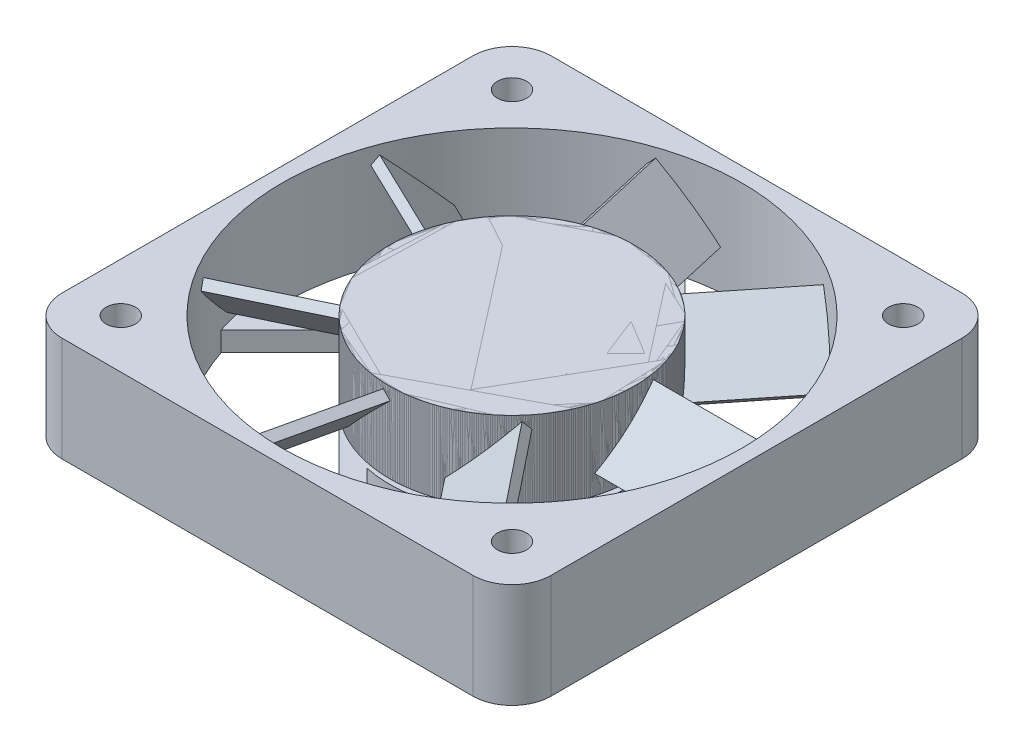
SolidWorks part; units mm, degrees
ref_plane "Front Plane" through (0, 0, 0) normal (0, 0, 1) x (1, 0, 0)
ref_plane "Top Plane" through (0, 0, 0) normal (0, 1, 0) x (1, 0, 0)
ref_plane "Right Plane" through (0, 0, 0) normal (1, 0, 0) x (0, 0, -1)
sketch "Sketch1" plane through (0, 0, 0) normal (0, 1, 0) x (1, 0, 0)
  line L0 (-25, 25) -> (25, -25) construction
  line L1 (-21, 25) -> (21, 25)
  line L2 (-25, 21) -> (-25, -21)
  line L3 (-21, -25) -> (21, -25)
  line L4 (25, 21) -> (25, -21)
  line L5 (20, 20) -> (-20, 20) construction
  line L6 (-20, 20) -> (-20, -20) construction
  line L7 (-20, -20) -> (20, -20) construction
  line L8 (20, -20) -> (20, 20) construction
  line L9 (-20, -20) -> (20, 20) construction
  circle A0 centre (0, 0) radius 23.5
  circle A1 centre (-20, 20) radius 1.5
  circle A2 centre (20, 20) radius 1.5
  circle A3 centre (20, -20) radius 1.5
  circle A4 centre (-20, -20) radius 1.5
  arc A5 (21, 25) -> (25, 21) centre (21, 21) cw
  arc A6 (21, -25) -> (25, -21) centre (21, -21) ccw
  arc A7 (-25, -21) -> (-21, -25) centre (-21, -21) ccw
  arc A8 (-21, 25) -> (-25, 21) centre (-21, 21) ccw
  point P17 (25, 25)
  dimension "D2" = 47
  dimension "D3" = 3
  dimension "D5" = 4
  dimension "D1" = 50
  dimension "D4" = 40
extrude "Boss-Extrude1" add sketch "Sketch1" along normal blind 10.7
sketch "Sketch2" plane through (0, 0, 0) normal (0, -1, 0) x (1, 0, 0)
  line L0 (-8.8388, 8.8388) -> (5.2324, 22.9101)
  line L1 (7.4414, 22.2907) -> (-2.6288, 12.2205)
  line L2 (0, 0) -> (0, 3.9858) construction
  line L3 (8.8388, 8.8388) -> (22.9101, -5.2324)
  line L4 (22.2907, -7.4414) -> (12.2205, 2.6288)
  line L5 (8.8388, -8.8388) -> (-5.2324, -22.9101)
  line L6 (-7.4414, -22.2907) -> (2.6288, -12.2205)
  line L7 (-8.8388, -8.8388) -> (-22.9101, 5.2324)
  line L8 (-22.2907, 7.4414) -> (-12.2205, -2.6288)
  arc A0 (-8.8388, 8.8388) -> (-12.2205, -2.6288) centre (0, 0) ccw
  circle A1 centre (0, 0) radius 23.5 construction
  arc A2 (7.4414, 22.2907) -> (5.2324, 22.9101) centre (0, 0) ccw
  arc A3 (22.2907, -7.4414) -> (22.9101, -5.2324) centre (0, 0) ccw
  arc A4 (-7.4414, -22.2907) -> (-5.2324, -22.9101) centre (0, 0) ccw
  arc A5 (-22.2907, 7.4414) -> (-22.9101, 5.2324) centre (0, 0) ccw
  arc A6 (8.8388, 8.8388) -> (-2.6288, 12.2205) centre (0, 0) ccw
  arc A7 (8.8388, -8.8388) -> (12.2205, 2.6288) centre (0, 0) ccw
  arc A8 (-8.8388, -8.8388) -> (2.6288, -12.2205) centre (0, 0) ccw
  point P24 (0, 0)
  dimension "D2" = 25
  dimension "D1" = 135
  dimension "D3" = 2
  dimension "D4" = 4
extrude "Boss-Extrude2" add sketch "Sketch2" against normal blind 2
sketch "Sketch3" plane through (0, 10.7, 0) normal (0, 1, 0) x (1, 0, 0)
  circle A0 centre (0, 0) radius 12.5
  dimension "D1" = 25
extrude "Boss-Extrude3" add sketch "Sketch3" against normal offset from surface (8.2 mm away) 0.5 separate body up to face at (0, 2, 0)
sketch "Sketch4" plane through (0, 0, 0) normal (1, 0, 0) x (0, 0, -1)
  line L0 (-3.5355, 4.4787) -> (2.1213, 10.1355)
  line L1 (-3.5355, 4.4787) -> (-2.8284, 3.7716)
  line L2 (2.1213, 10.1355) -> (2.8284, 9.4284)
  line L3 (-2.8284, 3.7716) -> (2.8284, 9.4284)
  line L4 (0, 0) -> (0, 6.6) construction
  line L5 (-21, 0) -> (21, 0) construction
  line L6 (0, 6.6) -> (12.5, 6.6) construction
  line L7 (12.5, 2.5) -> (12.5, 10.7) construction
  dimension "D1" = 45
  dimension "D2" = 1
  dimension "D3" = 8
extrude "Boss-Extrude4" add sketch "Sketch4" along normal offset from surface (22.902 mm away) 0.5
pattern_circular "CirPattern3" count 7 over 360 about axis through (0, 0, 0) along (0, 1, 0) of bodies 104
